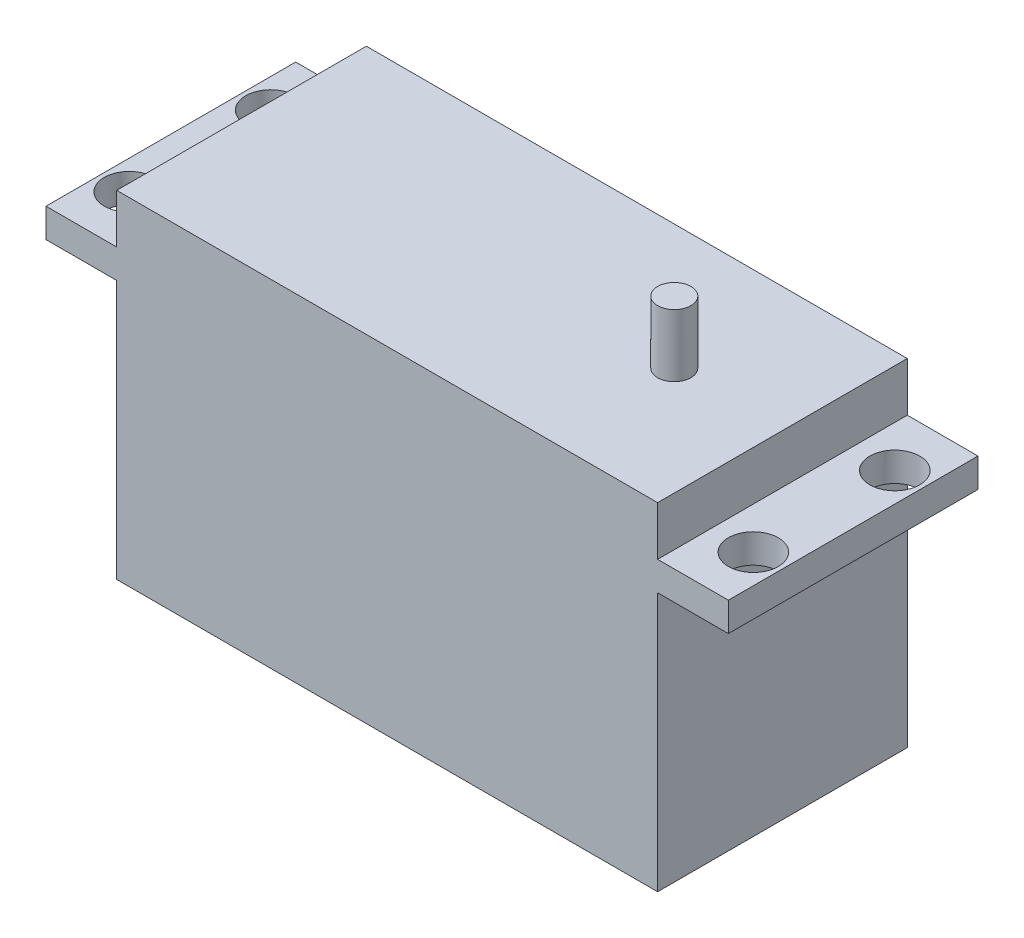
SolidWorks part; units mm, degrees
ref_plane "Front Plane" through (0, 0, 0) normal (0, 0, 1) x (1, 0, 0)
ref_plane "Top Plane" through (0, 0, 0) normal (0, 1, 0) x (1, 0, 0)
ref_plane "Right Plane" through (0, 0, 0) normal (1, 0, 0) x (0, 0, -1)
sketch "Sketch1" plane through (0, 0, 0) normal (0, 1, 0) x (1, 0, 0)
  line L1 (0, 0) -> (65, 0)
  line L2 (0, 0) -> (0, 30)
  line L3 (0, 30) -> (65, 30)
  line L4 (65, 0) -> (65, 30)
  dimension "D1" = 65
  dimension "D2" = 30
extrude "Boss-Extrude1" add sketch "Sketch1" along normal blind 40.5
sketch "Sketch2" plane through (65, 0, 0) normal (1, 0, 0) x (0, 0, -1)
  line L0 (0, 40.5) -> (0, 0) construction
  line L1 (0, 31.12) -> (30, 31.12)
  line L2 (0, 31.12) -> (0, 34.6)
  line L3 (0, 34.6) -> (30, 34.6)
  line L4 (30, 31.12) -> (30, 34.6)
  line L5 (30, 40.5) -> (30, 0) construction
  line L6 (0, 40.5) -> (30, 40.5) construction
  dimension "D1" = 5.9
  dimension "D2" = 3.48
extrude "Boss-Extrude2" add sketch "Sketch2" along normal blind 8.5 and the other way blind 73.5
sketch "Sketch3" plane through (0, 34.6, 0) normal (0, 1, 0) x (1, 0, 0)
  line L2 (-8.5, 30) -> (-8.5, 0) construction
  line L3 (73.5, 30) -> (73.5, 0) construction
  circle A0 centre (70, 23.5) radius 3
  circle A1 centre (70, 6.5) radius 3
  circle A2 centre (-5, 23.5) radius 3
  circle A3 centre (-5, 6.5) radius 3
  point P12 (-8.5, 15)
  dimension "D1" = 6
  dimension "D2" = 17
  dimension "D3" = 8.5
  dimension "D4" = 3.5
  dimension "D5" = 3.5
extrude "Cut-Extrude1" cut sketch "Sketch3" against normal through all
sketch "Sketch4" plane through (0, 40.5, 0) normal (0, 1, 0) x (1, 0, 0)
  line L0 (65, 0) -> (65, 30) construction
  line L3 (73.5, 30) -> (73.5, 0) construction
  circle A0 centre (52, 15) radius 2
  point P9 (73.5, 15)
  dimension "D1" = 4
  dimension "D2" = 13
extrude "Boss-Extrude3" add sketch "Sketch4" along normal blind 7.5
